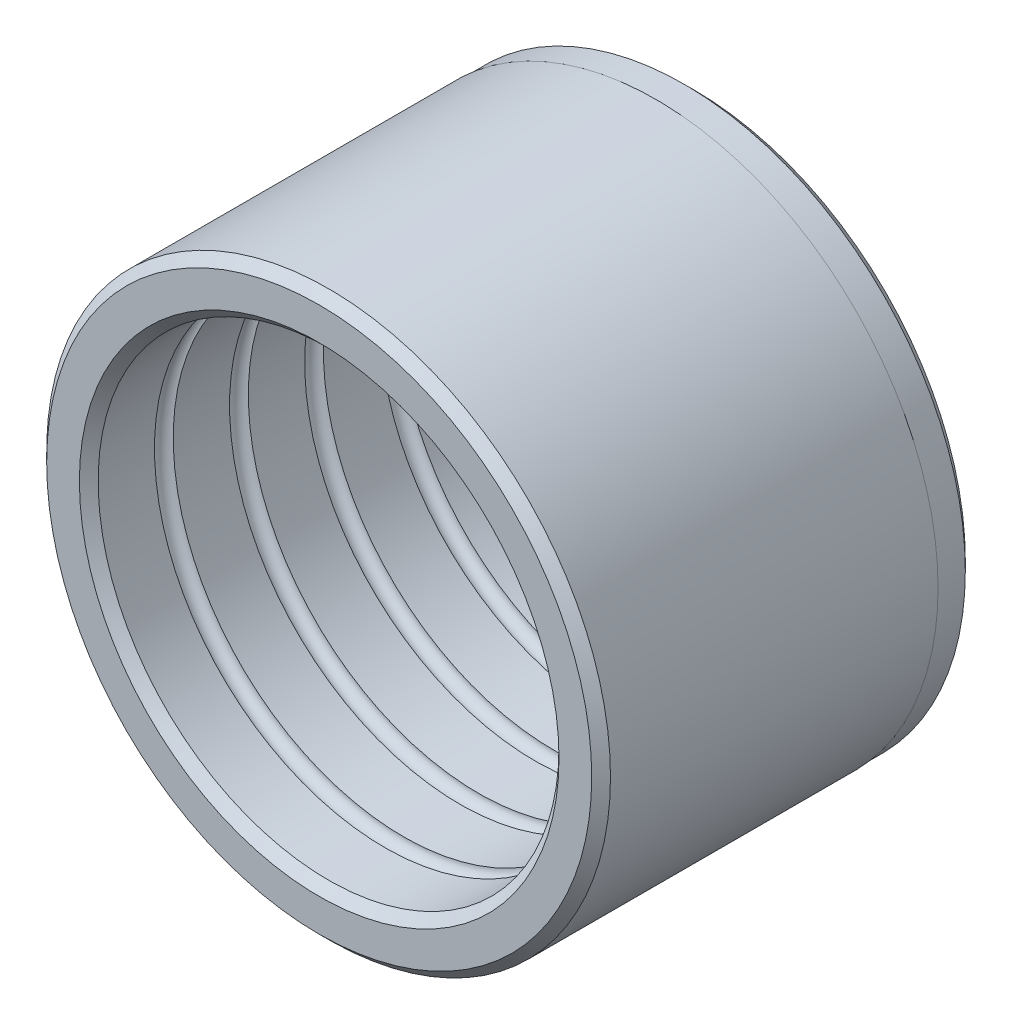
SolidWorks part; units mm, degrees
material "PB01 (C90710) Bronze"
ref_plane "Front" through (0, 0, 0) normal (0, 0, 1) x (1, 0, 0)
ref_plane "Top" through (0, 0, 0) normal (0, 1, 0) x (1, 0, 0)
ref_plane "Right" through (0, 0, 0) normal (1, 0, 0) x (0, 0, -1)
sketch "Sketch1" plane through (0, 0, 0) normal (1, 0, 0) x (0, 0, -1)
  line L0 (0, 0) -> (19.95, 0) construction
  line L1 (0.5, 15.0175) -> (17.95, 15.0175)
  line L2 (19.95, 12.775) -> (19.45, 12.275)
  line L3 (0.5, 12.275) -> (3.5, 12.275)
  line L4 (0, 14.5175) -> (0, 12.775)
  line L5 (19.95, 14.47) -> (19.95, 12.775)
  line L6 (19.45, 14.97) -> (19.95, 14.47)
  line L7 (0.5, 15.0175) -> (0, 14.5175)
  line L8 (17.95, 15.0175) -> (17.95, 14.97)
  line L9 (0, 12.275) -> (19.95, 12.275) construction
  line L10 (0, 12.775) -> (0.5, 12.275)
  line L11 (17.95, 14.97) -> (19.45, 14.97)
  line L13 (0, 14.97) -> (19.95, 14.97) construction
  line L14 (17.95, 15.0175) -> (17.95, 12.275) construction
  line L15 (0, 15.0175) -> (19.95, 15.0175) construction
  line L16 (19.95, 15.0175) -> (19.95, 12.275) construction
  line L33 (4.5, 12.275) -> (7.5, 12.275)
  line L34 (8.5, 12.275) -> (11.5, 12.275)
  line L35 (12.5, 12.275) -> (15.5, 12.275)
  line L36 (16.5, 12.275) -> (19.45, 12.275)
  arc A0 (15.5, 12.275) -> (16.5, 12.275) centre (16, 12.275) cw
  arc A1 (11.5, 12.275) -> (12.5, 12.275) centre (12, 12.275) cw
  arc A2 (7.5, 12.275) -> (8.5, 12.275) centre (8, 12.275) cw
  arc A3 (3.5, 12.275) -> (4.5, 12.275) centre (4, 12.275) cw
  point P5 (0, 12.425)
  point P6 (20, 12.425)
  point P9 (0, 12.275)
  point P18 (16, 14.8)
  point P19 (16, 12.25)
  point P20 (12, 14.8)
  point P21 (12, 12.25)
  point P22 (8, 14.8)
  point P23 (8, 12.25)
  point P24 (4, 14.8)
  point P25 (4, 12.25)
  point P42 (0, 15.0175)
  point P44 (19.95, 14.97)
  point P46 (19.95, 12.275)
  point P50 (4, 12.775)
  point P51 (8, 12.775)
  point P52 (12, 12.775)
  point P53 (16, 12.775)
  dimension "D4" = 0.5
  dimension "D8" = 0.5
  dimension "D9" = 0.5
  dimension "D10" = 0.5
  dimension "D1" = 19.95
  dimension "D2" = 24.55
  dimension "D3" = 30.035
  dimension "D5" = 29.94
  dimension "D6" = 25.55
  dimension "D7" = 2
  dimension "D11" = 4
  dimension "D12" = 4
  dimension "D13" = 4
  dimension "D14" = 4
  dimension "D15" = 25.55
  dimension "D16" = 25.55
  dimension "D17" = 25.55
revolve "Revolve1" add sketch "Sketch1" angle 360 about L0
